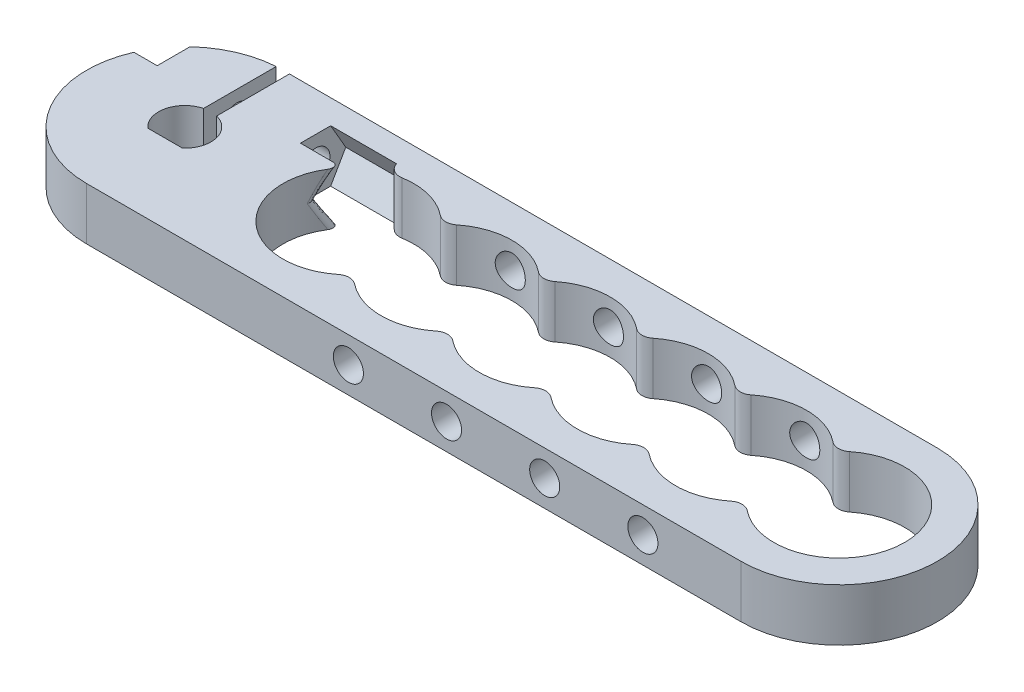
SolidWorks part; units mm, degrees
material "ABS"
ref_plane "Спереди" through (0, 0, 0) normal (0, 0, 1) x (1, 0, 0)
ref_plane "Сверху" through (0, 0, 0) normal (0, 1, 0) x (1, 0, 0)
ref_plane "Справа" through (0, 0, 0) normal (1, 0, 0) x (0, 0, -1)
sketch "Эскиз2" plane through (0, 0, 0) normal (0, 1, 0) x (1, 0, 0)
  line L0 (0, 0) -> (50, 0) construction
  line L1 (0, 7.5) -> (50, 7.5)
  line L2 (0, -7.5) -> (50, -7.5)
  line L3 (-1.3229, -1.5) -> (1.3229, -1.5)
  circle A0 centre (0, 0) radius 2
  arc A1 (0, 7.5) -> (0, -7.5) centre (0, 0) ccw
  arc A2 (50, -7.5) -> (50, 7.5) centre (50, 0) ccw
  circle A3 centre (50, 0) radius 5
  circle A4 centre (42.5, 0) radius 5
  circle A5 centre (35, 0) radius 5
  circle A6 centre (27.5, 0) radius 5
  circle A7 centre (20, 0) radius 5
  circle A8 centre (12.5, 0) radius 5
  point P4 (25, 0)
  point P13 (14.3172, 3.1454)
  dimension "D1" = 4
  dimension "D4" = 15
  dimension "D5" = 10
  dimension "D2" = 50
  dimension "D3" = 3.5
  dimension "D7" = 7.5
  dimension "D6" = 6
extrude "Бобышка-Вытянуть1" add sketch "Эскиз2" along normal blind 4
sketch "Эскиз3" plane through (0, 4, 0) normal (0, 1, 0) x (1, 0, 0)
  line L1 (-0.5, 0) -> (0.5, 0)
  line L2 (-0.5, 0) -> (-0.5, 9.1112)
  line L3 (-0.5, 9.1112) -> (0.5, 9.1112)
  line L4 (0.5, 0) -> (0.5, 9.1112)
  line L5 (0, 9.1112) -> (0, 0) construction
  line L6 (-0.5, 4.5556) -> (0.5, 4.5556) construction
  point P4 (0.5, 9.4552)
  point P140 (0, 4.5556)
  dimension "D1" = 1
extrude "Вырез-Вытянуть1" cut sketch "Эскиз3" against normal through all
ref_plane "Плоскость1" through (-7.5, 0, 0) normal (-1, 0, 0) x (0, 0, 1)
hole_wizard "Цековка для винта с внутренним шестигранником M21" positions "Эскиз6" profile "Эскиз8" counterbore size "M2" standard "DIN"
sketch "Эскиз6" plane through (-7.5, 0, 0) normal (-1, 0, 0) x (0, 0, 1)
  line L0 (-7.5, 4) -> (-7.4833, 0) construction
  line L2 (-6.9911, 2) -> (49993.0089, 2) construction
  point P0 (-4.4916, 2)
  point P12 (-7.4917, 2)
  point P14 (0, 0)
  dimension "D1" = 3
sketch "Эскиз8" plane through (-7.5, 2, -4.4916) normal (0, 1, 0) x (0, 0, 1)
  line L0 (0, 0) -> (0, 15.6609)
  line L1 (0, 15.6609) -> (1.1, 15)
  line L2 (1.1, 15) -> (1.1, 2.4)
  line L3 (1.1, 2.4) -> (2.5, 2.4)
  line L4 (2.5, 2.4) -> (2.5, 0)
  line L5 (2.5, 0) -> (0, 0)
  line L10 (0, 15.6609) -> (-1.1, 15) construction
  line L11 (0, -6.35) -> (0, 107.95) construction
  dimension "Диаметр отверстия" = 2.2
  dimension "Глубина отверстия" = 15
  dimension "Диаметр цековки" = 5
  dimension "Глубина цековки" = 2.4
  dimension "Угол заточки сверла" = 118
sketch "Эскиз9" plane through (-7.5, 0, 0) normal (-1, 0, 0) x (0, 0, 1)
  line L1 (-6.801, 2) -> (-5.6463, 0)
  line L2 (-5.6463, 0) -> (-3.3369, 0)
  line L3 (-3.3369, 0) -> (-2.1822, 2)
  line L4 (-2.1822, 2) -> (-3.3369, 4)
  line L5 (-3.3369, 4) -> (-5.6463, 4)
  line L6 (-5.6463, 4) -> (-6.801, 2)
  circle A0 centre (-4.4916, 2) radius 2 construction
  dimension "D1" = 4
extrude "Вырез-Вытянуть2" cut sketch "Эскиз9" against normal blind 5 from offset 13 offset against normal yes
fillet "Скругление1" radius 1 1 edges at (10.5, 2, -4.5826)
fillet "Скругление2" radius 0.4 2 edges at (8.3486, 3.0469, -2.7867) (8.3486, 0.9531, -2.7867)
fillet "Скругление3" radius 1 10 edges at (16.25, 2, -3.3072) (16.25, 2, 3.3072) (23.75, 2, -3.3072) (23.75, 2, 3.3072) (31.25, 2, 3.3072) (31.25, 2, -3.3072) (38.75, 2, 3.3072) (38.75, 2, -3.3072) (46.25, 2, 3.3072) (46.25, 2, -3.3072)
hole_wizard "Сверло под метчик  спиральное M2.21" positions "Эскиз10" profile "Эскиз12" hole size "M2.2x0.45" standard "DIN"
sketch "Эскиз10" plane through (0, 0, -7.5) normal (0, 0, -1) x (-1, 0, 0)
  line L0 (-39.375, 0) -> (-39.375, 4) construction
  line L1 (-45.625, 4) -> (-45.625, 0) construction
  line L2 (-39.375, 0) -> (-39.375, 4) construction
  line L3 (-45.625, 4) -> (-45.625, 0) construction
  line L4 (-45.625, 4) -> (-39.375, 0) construction
  point P9 (-42.5, 2)
  point P16 (-35, 2)
  point P17 (-27.5, 2)
  point P18 (-20, 2)
  dimension "D1" = 4
sketch "Эскиз12" plane through (20, 2, -7.5) normal (1, 0, 0) x (0, 1, 0)
  line L0 (0, 0) -> (0, 15.691)
  line L1 (0, 15.691) -> (1.15, 15)
  line L2 (1.15, 15) -> (1.15, 0)
  line L5 (1.15, 0) -> (0, 0)
  line L10 (0, 15.691) -> (-1.15, 15) construction
  line L11 (0, -6.35) -> (0, 107.95) construction
  dimension "Диаметр отверстия" = 2.3
  dimension "Глубина отверстия" = 15
  dimension "Угол заточки сверла" = 118
